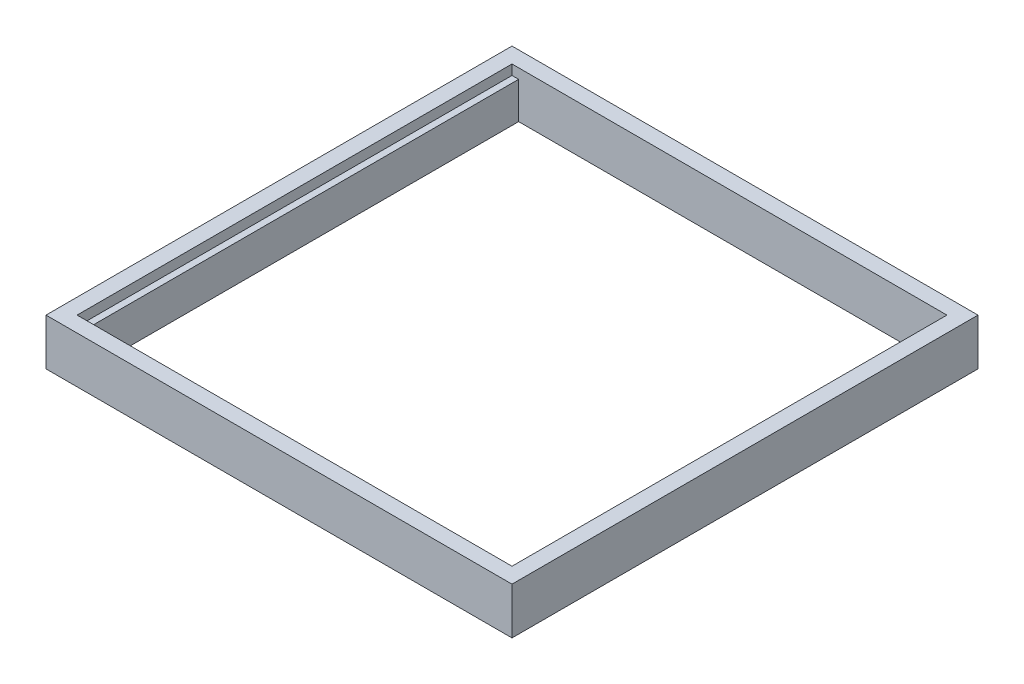
SolidWorks part; units mm, degrees
ref_plane "Front Plane" through (0, 0, 0) normal (0, 0, 1) x (1, 0, 0)
ref_plane "Top Plane" through (0, 0, 0) normal (0, 1, 0) x (1, 0, 0)
ref_plane "Right Plane" through (0, 0, 0) normal (1, 0, 0) x (0, 0, -1)
sketch "Sketch1" plane through (0, 0, 0) normal (0, 1, 0) x (1, 0, 0)
  line L1 (-37.5, -37.5) -> (37.5, -37.5)
  line L2 (-37.5, -37.5) -> (-37.5, 37.5)
  line L3 (-37.5, 37.5) -> (37.5, 37.5)
  line L4 (37.5, -37.5) -> (37.5, 37.5)
  line L5 (-37.5, -37.5) -> (37.5, 37.5) construction
  line L6 (-37.5, 37.5) -> (37.5, -37.5) construction
  point P0 (0, 0)
  dimension "D1" = 75
  dimension "D2" = 75
extrude "Base" add sketch "Sketch1" along normal blind 7.5
sketch "Sketch2" plane through (0, 7.5, 0) normal (0, 1, 0) x (1, 0, 0)
  line L0 (0, -4.125) -> (0, 4.125) construction
  line L1 (-35, -35) -> (35, -35)
  line L2 (-35, -35) -> (-35, 35)
  line L3 (-35, 35) -> (35, 35)
  line L4 (35, -35) -> (35, 35)
  line L5 (-35, -35) -> (35, 35) construction
  line L6 (-35, 35) -> (35, -35) construction
  line L7 (0, -4.125) -> (0, 4.125) construction
  point P0 (0, 0)
  point P1 (0, 0)
  dimension "D1" = 70
  dimension "D2" = 70
extrude "Slot" cut sketch "Sketch2" against normal blind 1.6
sketch "Sketch3" plane through (0, 5.9, 0) normal (0, 1, 0) x (1, 0, 0)
  line L6 (-33.929, -35) -> (33.929, -35)
  line L7 (-33.929, -35) -> (-33.929, 35)
  line L8 (-33.929, 35) -> (33.929, 35)
  line L9 (33.929, -35) -> (33.929, 35)
  line L10 (-33.929, -35) -> (33.929, 35) construction
  line L11 (-33.929, 35) -> (33.929, -35) construction
  line L12 (-35, 35) -> (35, -35) construction
  line L13 (-35, -35) -> (35, 35) construction
  line L16 (-35, -35) -> (35, -35) construction
  line L17 (35, 35) -> (-35, 35) construction
  point P2 (0, 37.5)
  point P4 (0, 0)
  point P8 (0, 0)
  point P15 (-33.929, 35)
extrude "Slot-Components" cut sketch "Sketch3" against normal up to surface (5.9 mm away) up to face at (0, 0, 0)
